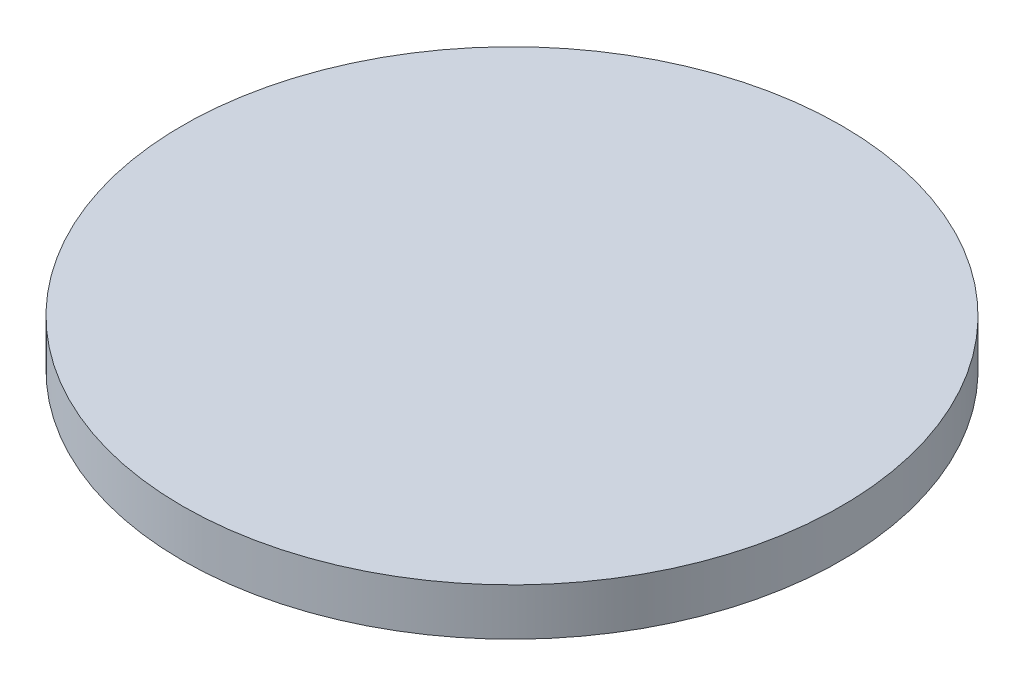
SolidWorks part; units mm, degrees
ref_plane "Ön Düzlem" through (0, 0, 0) normal (0, 0, 1) x (1, 0, 0)
ref_plane "Üst Düzlem" through (0, 0, 0) normal (0, 1, 0) x (1, 0, 0)
ref_plane "Sağ Düzlem" through (0, 0, 0) normal (1, 0, 0) x (0, 0, -1)
sketch "Çizim1" plane through (0, 0, 0) normal (0, 1, 0) x (1, 0, 0)
  circle A0 centre (0, 0) radius 28
extrude "Yükseklik-Ekstrüzyon1" add sketch "Çizim1" along normal blind 4
